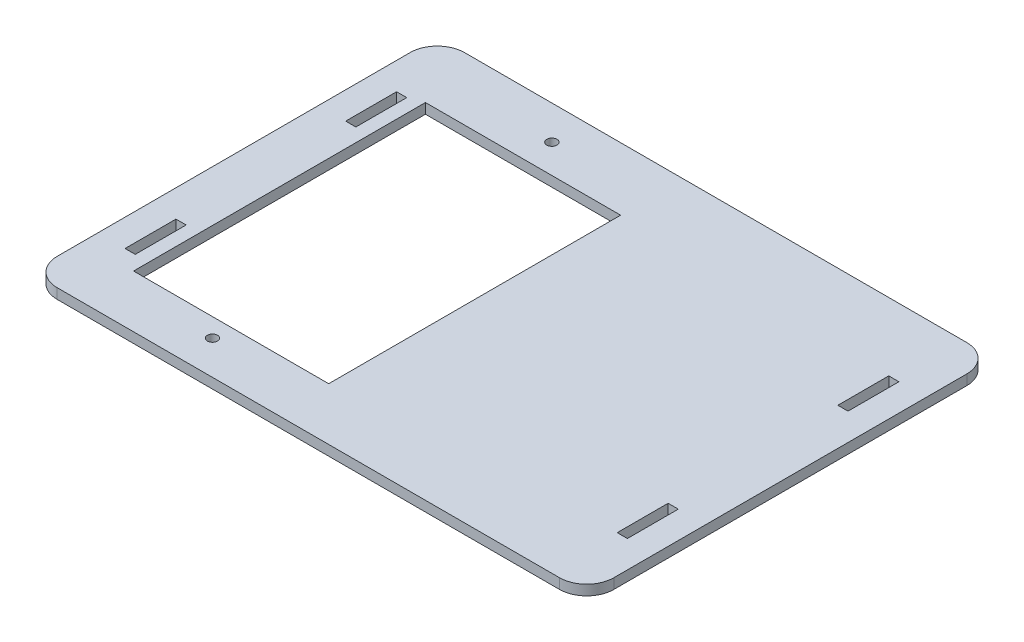
SolidWorks part; units mm, degrees
material "ABS"
ref_plane "Front Plane" through (0, 0, 0) normal (0, 0, 1) x (1, 0, 0)
ref_plane "Top Plane" through (0, 0, 0) normal (0, 1, 0) x (1, 0, 0)
ref_plane "Right Plane" through (0, 0, 0) normal (1, 0, 0) x (0, 0, -1)
sketch "Sketch1" plane through (0, 0, 0) normal (0, 1, 0) x (1, 0, 0)
  line L0 (0, 60) -> (0, 0) construction
  line L1 (-74, 60) -> (74, 60)
  line L2 (-82, 52) -> (-82, -52)
  line L3 (-74, -60) -> (74, -60)
  line L4 (82, 52) -> (82, -52)
  line L5 (0, 0) -> (0, -60) construction
  arc A0 (74, 60) -> (82, 52) centre (74, 52) cw
  arc A1 (74, -60) -> (82, -52) centre (74, -52) ccw
  arc A2 (-74, -60) -> (-82, -52) centre (-74, -52) cw
  arc A3 (-82, 52) -> (-74, 60) centre (-74, 52) cw
  dimension "D1" = 8
  dimension "D2" = 120
  dimension "D3" = 164
extrude "Boss-Extrude1" add sketch "Sketch1" along normal blind 3
sketch "Sketch2" plane through (0, 3, 0) normal (0, 1, 0) x (1, 0, 0)
  line L0 (0, 37) -> (0, 40) construction
  line L1 (-44.5, 40) -> (41.5, 40) construction
  line L2 (-44.5, 40) -> (-44.5, -17.5) construction
  line L3 (-44.5, -17.5) -> (41.5, -17.5) construction
  line L4 (41.5, 40) -> (41.5, -17.5) construction
  line L5 (74, 60) -> (-74, 60) construction
  line L6 (57, -60) -> (57, -40) construction
  line L7 (-74, -60) -> (74, -60) construction
  line L8 (82, -52) -> (82, 52) construction
  line L9 (0, -14.5) -> (0, -17.5) construction
  line L10 (-38.5, 37) -> (38.5, 37) construction
  line L11 (-38.5, 37) -> (-38.5, -14.5) construction
  line L12 (-38.5, -14.5) -> (38.5, -14.5) construction
  line L13 (38.5, 37) -> (38.5, -14.5) construction
  line L14 (0, 0) -> (0, 37) construction
  line L15 (-82, 52) -> (-82, -52) construction
  line L16 (57, -40) -> (82, -40) construction
  line L17 (57, -40) -> (57, -26.5) construction
  line L18 (-67, 0) -> (-64, 0) construction
  line L19 (-64, -38.5) -> (-12.5, -38.5) construction
  line L20 (-64, -38.5) -> (-64, 38.5) construction
  line L21 (-64, 38.5) -> (-12.5, 38.5) construction
  line L22 (-12.5, -38.5) -> (-12.5, 38.5) construction
  line L23 (-67, 41.5) -> (-9.5, 41.5)
  line L24 (-67, 41.5) -> (-67, -44.5)
  line L25 (-67, -44.5) -> (-9.5, -44.5)
  line L26 (-9.5, 41.5) -> (-9.5, -44.5)
  line L27 (-12.5, 0) -> (-9.5, 0) construction
  line L28 (-67, 0) -> (-82, 0) construction
  line L29 (-38.25, -50) -> (-38.25, -38.5) construction
  line L30 (-38.25, 38.5) -> (-38.25, 50) construction
  circle A0 centre (57, -40) radius 10.25 construction
  circle A1 centre (-38.25, 50) radius 1.5
  circle A2 centre (-38.25, -50) radius 1.5
  dimension "D4" = 20.5
  dimension "D21" = 3
  dimension "D1" = 57.5
  dimension "D2" = 86
  dimension "D3" = 20
  dimension "D5" = 6
  dimension "D6" = 3
  dimension "D7" = 3
  dimension "D8" = 43.5
  dimension "D9" = 43.5
  dimension "D10" = 25
  dimension "D11" = 51.5
  dimension "D12" = 77
  dimension "D13" = 33.5
  dimension "D14" = 20
  dimension "D15" = 3
  dimension "D16" = 3
  dimension "D17" = 6
  dimension "D18" = 86
  dimension "D19" = 57.5
  dimension "D20" = 15
  dimension "D22" = 100
extrude "Cut-Extrude1" cut sketch "Sketch2" against normal through all
sketch "Sketch3" plane through (0, 3, 0) normal (0, 1, 0) x (1, 0, 0)
  line L0 (-71, 25) -> (-71, -25) construction
  line L1 (-74, 40) -> (-71, 40)
  line L2 (-74, 40) -> (-74, 25)
  line L3 (-74, 25) -> (-71, 25)
  line L4 (-71, 40) -> (-71, 25)
  line L5 (-74, -25) -> (-71, -25)
  line L6 (-74, -25) -> (-74, -40)
  line L7 (-74, -40) -> (-71, -40)
  line L8 (-71, -25) -> (-71, -40)
  line L9 (-71, 0) -> (0, 0) construction
  line L10 (-82, 52) -> (-82, -52) construction
  line L11 (0, 0) -> (0, 40) construction
  line L13 (71, -25) -> (71, -40)
  line L14 (74, -40) -> (71, -40)
  line L15 (74, -25) -> (74, -40)
  line L16 (74, -25) -> (71, -25)
  line L17 (71, 40) -> (71, 25)
  line L18 (74, 25) -> (71, 25)
  line L19 (74, 40) -> (74, 25)
  line L20 (74, 40) -> (71, 40)
  dimension "D1" = 3
  dimension "D2" = 15
  dimension "D3" = 8
  dimension "D4" = 50
  dimension "D5" = 40
extrude "Cut-Extrude2" cut sketch "Sketch3" against normal through all
sketch "Sketch4" plane through (0, 3, 0) normal (0, 1, 0) x (1, 0, 0)
  line L0 (-72.5, 0) -> (0, 0) construction
  line L1 (0, 0) -> (72.5, 0) construction
  line L2 (-72.5, 25) -> (-72.5, 0) construction
  line L3 (-74, 25) -> (-71, 25) construction
  circle A0 centre (-72.5, 0) radius 1.5
  circle A1 centre (72.5, 0) radius 1.5
  dimension "D1" = 3
extrude "Cut-Extrude3" [suppressed] cut sketch "Sketch4" against normal through all
sketch "Sketch5" plane through (0, 3, 0) normal (0, 1, 0) x (1, 0, 0)
  line L0 (-62, -56) -> (-62, -60)
  line L1 (-74, -60) -> (74, -60) construction
  line L2 (-62, -60) -> (-57, -60)
  line L3 (-57, -60) -> (-57, -56)
  line L4 (-82, 52) -> (-82, -52) construction
  arc A0 (-57, -56) -> (-62, -56) centre (-59.5, -56) ccw
  dimension "D1" = 5
  dimension "D2" = 4
  dimension "D3" = 20
extrude "Cut-Extrude4" [suppressed] cut sketch "Sketch5" against normal through all
sketch "Sketch6" [suppressed] plane through (0, 3, 0) normal (0, 1, 0) x (1, 0, 0)
  line L0 (-11.25, -48.5) -> (11.25, -48.5) construction
  line L1 (0, 0) -> (0, -48.5) construction
  circle A0 centre (-11.25, -48.5) radius 1.5
  circle A1 centre (11.25, -48.5) radius 1.5
  dimension "D1" = 3
extrude "Cut-Extrude5" [suppressed] cut sketch "Sketch6" against normal through all
ref_plane "Plane1" through (0, 0, 1.5) normal (0, 0, 1) x (1, 0, 0)
ref_plane "Plane2" through (-38.25, 0, 0) normal (-1, 0, 0) x (0, 0, 1)
